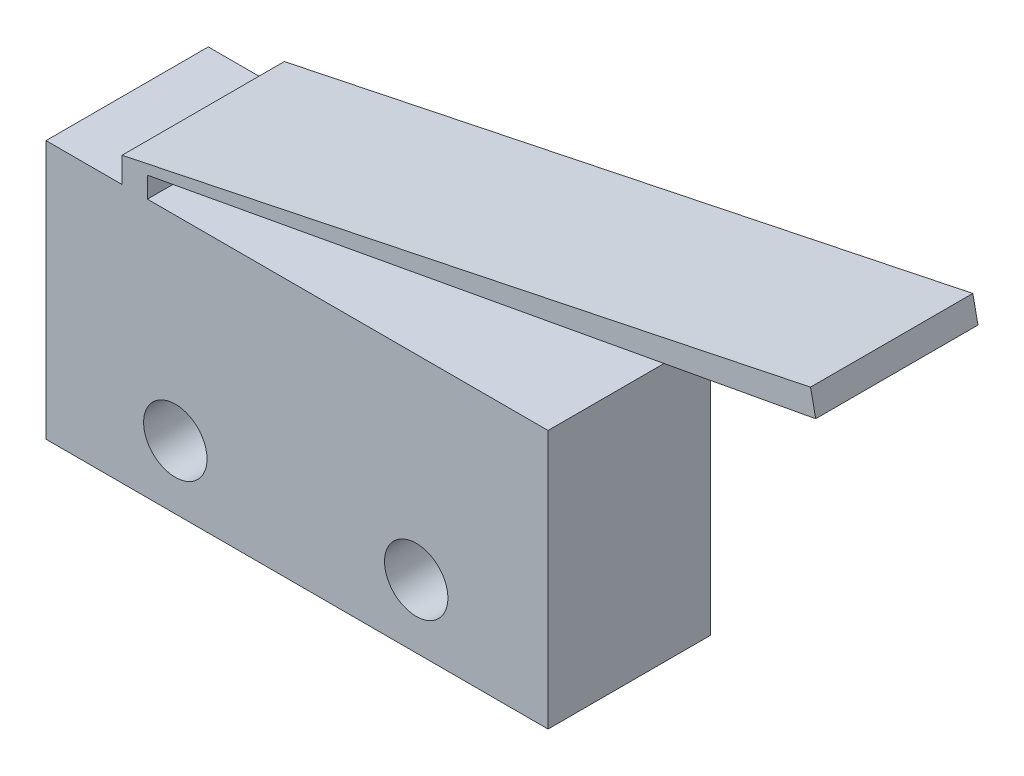
SolidWorks part; units mm, degrees
ref_plane "前视基准面" through (0, 0, 0) normal (0, 0, 1) x (1, 0, 0)
ref_plane "上视基准面" through (0, 0, 0) normal (0, 1, 0) x (1, 0, 0)
ref_plane "右视基准面" through (0, 0, 0) normal (1, 0, 0) x (0, 0, -1)
other "Configuration Table"
sketch "草图1" plane through (0, 0, 0) normal (0, 0, 1) x (1, 0, 0)
  line L0 (-2.1, 7.7) -> (-2.1, 8.7)
  line L1 (-5.1, 7.7) -> (14.7, 7.7)
  line L2 (-5.1, 7.7) -> (-5.1, -2.5)
  line L3 (-5.1, -2.5) -> (14.7, -2.5)
  line L4 (14.7, 7.7) -> (14.7, -2.5)
  line L5 (-2.1, 8.7) -> (25.0521, 14.3567)
  line L6 (25.0521, 14.3567) -> (25.2561, 13.3777)
  line L7 (25.2561, 13.3777) -> (-1.1, 8.52)
  line L8 (-1.1, 8.52) -> (-1.1, 7.7)
  line L9 (-2.1, 8.7) -> (-1.1, 8.52) construction
  line L10 (-1.1, 8.52) -> (25.7, 8.52) construction
  circle A0 centre (0, 0) radius 1.25
  circle A1 centre (9.5, 0) radius 1.25
  point P11 (-2.1, 8.2)
  dimension "D1" = 2.5
  dimension "D2" = 9.5
  dimension "D3" = 2.5
  dimension "D5" = 5.1
  dimension "D4" = 10.2
  dimension "D6" = 19.8
  dimension "D7" = 1
  dimension "D8" = 1
  dimension "D9" = 3
  dimension "D10" = 1
  dimension "D11" = 11
extrude "凸台-拉伸1" add sketch "草图1" along normal blind 6.4 contours L4 L1 L2 L3 A1 A0 | L9 L0 L1 L8 | L5 L9 L7 L6
